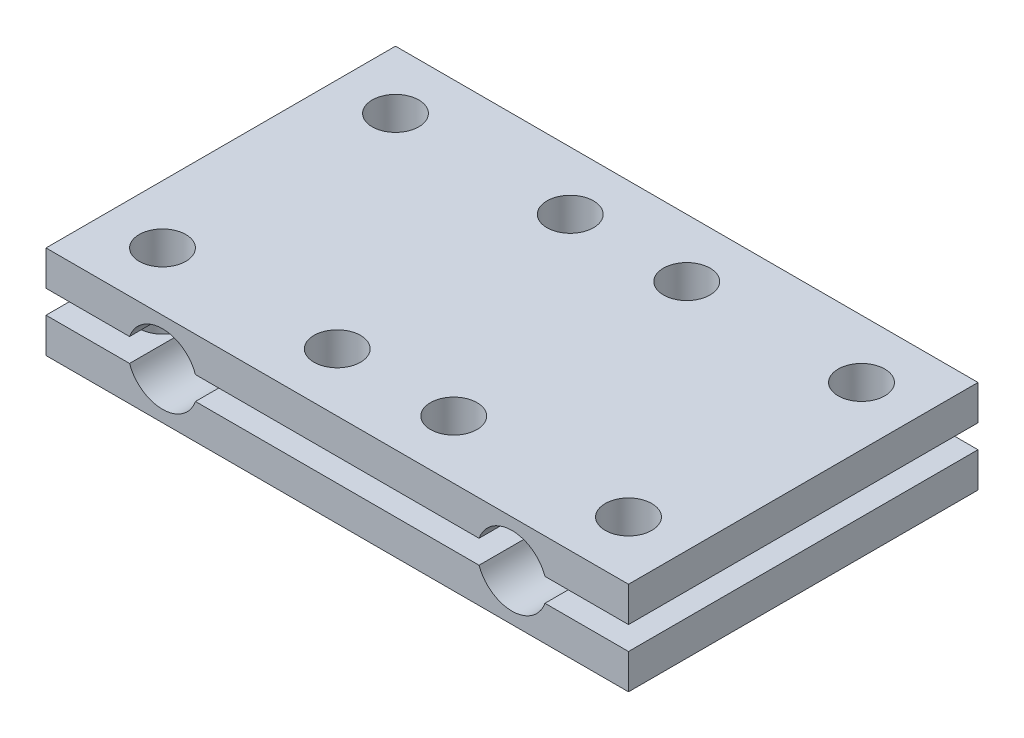
SolidWorks part; units mm, degrees
ref_plane "정면" through (0, 0, 0) normal (0, 0, 1) x (1, 0, 0)
ref_plane "윗면" through (0, 0, 0) normal (0, 1, 0) x (1, 0, 0)
ref_plane "우측면" through (0, 0, 0) normal (1, 0, 0) x (0, 0, -1)
sketch "스케치1" plane through (0, 0, 0) normal (0, 1, 0) x (1, 0, 0)
  line L0 (-12.5, 30) -> (-12.5, 0) construction
  line L1 (0, 0) -> (25, 0)
  line L2 (0, 0) -> (0, 30)
  line L3 (0, 30) -> (25, 30)
  line L4 (25, 0) -> (25, 30)
  line L5 (0, 0) -> (-25, 0)
  line L6 (0, 0) -> (0, 30)
  line L7 (0, 30) -> (-25, 30)
  line L8 (-25, 0) -> (-25, 30)
  line L9 (-20, 30) -> (-20, 0) construction
  line L10 (-25, 15) -> (25, 15) construction
  circle A0 centre (-20, 25) radius 2
  circle A1 centre (-20, 5) radius 2
  circle A2 centre (-5, 5) radius 2
  circle A3 centre (-5, 25) radius 2
  circle A4 centre (5, 5) radius 2
  circle A5 centre (5, 25) radius 2
  circle A6 centre (20, 5) radius 2
  circle A7 centre (20, 25) radius 2
  dimension "D3" = 4
  dimension "D1" = 25
  dimension "D2" = 30
  dimension "D4" = 20
  dimension "D5" = 5
extrude "보스-돌출1" add sketch "스케치1" along normal blind 8 contours L8 L5 L2 L7 A1 A0 A2 A3 | L1 L4 L3 L2 A4 A5 A6 A7
sketch "스케치2" plane through (0, 0, 0) normal (0, 0, 1) x (1, 0, 0)
  line L0 (0, 0) -> (0, 8) construction
  line L1 (25, 8) -> (-25, 8) construction
  line L2 (-15, 8) -> (-15, 0) construction
  line L3 (15, 8) -> (15, 0) construction
  line L4 (25, 8) -> (25, 0) construction
  line L5 (-25, 5) -> (25, 5)
  line L6 (-25, 5) -> (-25, 3)
  line L7 (-25, 3) -> (25, 3)
  line L8 (25, 5) -> (25, 3)
  line L9 (-25, 5) -> (25, 3) construction
  line L10 (-25, 3) -> (25, 5) construction
  line L11 (25, 5) -> (-25, 3) construction
  line L12 (25, 3) -> (-25, 5) construction
  line L13 (25, 5) -> (25, 3)
  line L14 (-25, 5) -> (-25, 3)
  circle A0 centre (-15, 4) radius 3
  circle A1 centre (15, 4) radius 3
  point P11 (0, 4)
  line M5 (25, 0) -> (25, 8)
  line M7 (-25, 8) -> (-25, 0)
  dimension "D2" = 6
  dimension "D1" = 30
  dimension "D3" = 2
extrude "컷-돌출1" cut sketch "스케치2" against normal through all contours L7 A1 L5 A0 | A0 L5 L7 M7 | L5 A1 L7 M5
